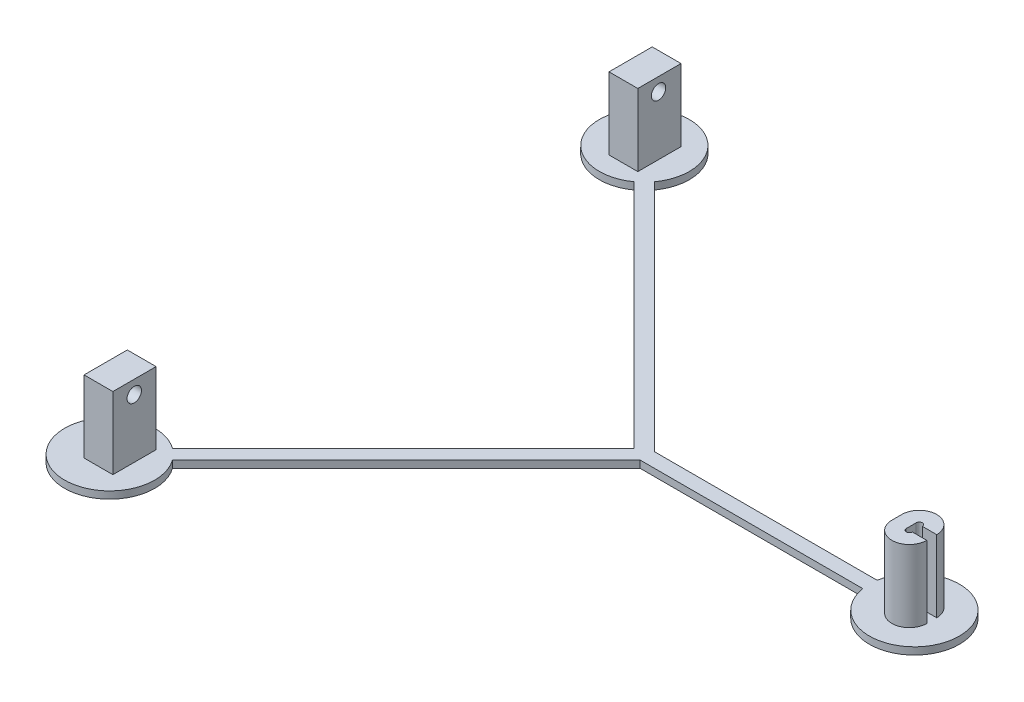
SolidWorks part; units mm, degrees
ref_plane "前视基准面" through (0, 0, 0) normal (0, 0, 1) x (1, 0, 0)
ref_plane "上视基准面" through (0, 0, 0) normal (0, 1, 0) x (1, 0, 0)
ref_plane "右视基准面" through (0, 0, 0) normal (1, 0, 0) x (0, 0, -1)
sketch "Sketch1" plane through (0, 0, 0) normal (0, 1, 0) x (1, 0, 0)
  line L8 (75.0746, 80.2538) -> (10.1392, 145.1892)
  line L9 (75.0746, 76.2538) -> (136.9072, 76.2538)
  line L10 (71.4178, 78.2538) -> (7.3108, 14.1468)
  line L11 (74.2462, 78.2538) -> (8.8388, 143.6612) construction
  line L12 (74.2462, 78.2538) -> (8.8388, 12.8464) construction
  line L13 (74.2462, 78.2538) -> (136.7462, 78.2538) construction
  line L14 (71.4178, 78.2538) -> (7.3108, 142.3608)
  line L15 (75.0746, 80.2538) -> (136.9072, 80.2538)
  line L16 (75.0746, 76.2538) -> (10.1392, 11.3183)
  arc A0 (136.9072, 76.2538) -> (136.9072, 80.2538) centre (149.2462, 78.2538) ccw
  arc A2 (10.1392, 145.1892) -> (7.3108, 142.3608) centre (0, 152.5) ccw
  arc A4 (7.3108, 14.1468) -> (10.1392, 11.3183) centre (0, 4.0076) ccw
  dimension "D4" = 135
  dimension "D5" = 75
  dimension "D6" = 105
  dimension "D7" = 105
extrude "Boss-Extrude1" add sketch "Sketch1" along normal blind 2
sketch "Sketch2" plane through (0, 2, 0) normal (0, 1, 0) x (1, 0, 0)
  line L0 (149.3462, 76.7538) -> (149.3462, 79.5038) construction
  line L1 (5.3815, 11.5218) -> (5.3815, 170.2838) construction
  line L2 (144.4962, 76.7538) -> (144.4962, 79.5038)
  line L3 (148.4962, 76.7538) -> (148.4962, 79.5038)
  line L4 (150.1962, 76.7538) -> (150.1962, 79.5038)
  line L5 (5.3815, 11.5218) -> (-2.6185, 11.5218)
  line L6 (5.3815, 11.5218) -> (5.3815, -0.4782)
  line L7 (5.3815, -0.4782) -> (-2.6185, -0.4782)
  line L8 (-2.6185, 11.5218) -> (-2.6185, -0.4782)
  line L9 (154.1962, 76.7538) -> (154.1962, 79.5038)
  line L14 (5.3815, 157.3042) -> (-2.6185, 157.3042)
  line L15 (5.3815, 157.3042) -> (5.3815, 145.3042)
  line L16 (5.3815, 145.3042) -> (-2.6185, 145.3042)
  line L17 (-2.6185, 157.3042) -> (-2.6185, 145.3042)
  arc A1 (148.4962, 76.7538) -> (150.1962, 76.7538) centre (149.3462, 76.7538) ccw
  arc A2 (150.1962, 79.5038) -> (148.4962, 79.5038) centre (149.3462, 79.5038) ccw
  arc A3 (154.1962, 79.5038) -> (144.4962, 79.5038) centre (149.3462, 79.5038) ccw
  arc A4 (144.4962, 76.7538) -> (154.1962, 76.7538) centre (149.3462, 76.7538) ccw
  point P5 (149.3462, 78.1288)
  dimension "D1" = 4
  dimension "D2" = 2.75
  dimension "D3" = 1.7
  dimension "D4" = 8
  dimension "D5" = 12
extrude "Boss-Extrude2" add sketch "Sketch2" along normal blind 20
sketch "Sketch6" plane through (0, 22, 0) normal (0, 1, 0) x (1, 0, 0)
  line L1 (150.1962, 79.5038) -> (154.1962, 79.5038)
  line L2 (150.1962, 79.5038) -> (150.1962, 76.7538)
  line L3 (150.1962, 76.7538) -> (154.1962, 76.7538)
  line L4 (154.1962, 79.5038) -> (154.1962, 76.7538)
extrude "Cut-Extrude3" cut sketch "Sketch6" against normal blind 20
sketch "Sketch7" plane through (-2.6185, 0, 0) normal (-1, 0, 0) x (0, 0, 1)
  line L0 (-78.2538, 0) -> (-78.2538, 55.9621) construction
  circle A0 centre (-5.4541, 18.2969) radius 2
  circle A1 centre (-151.0535, 18.2969) radius 2
extrude "Cut-Extrude4" cut sketch "Sketch7" against normal blind 10
